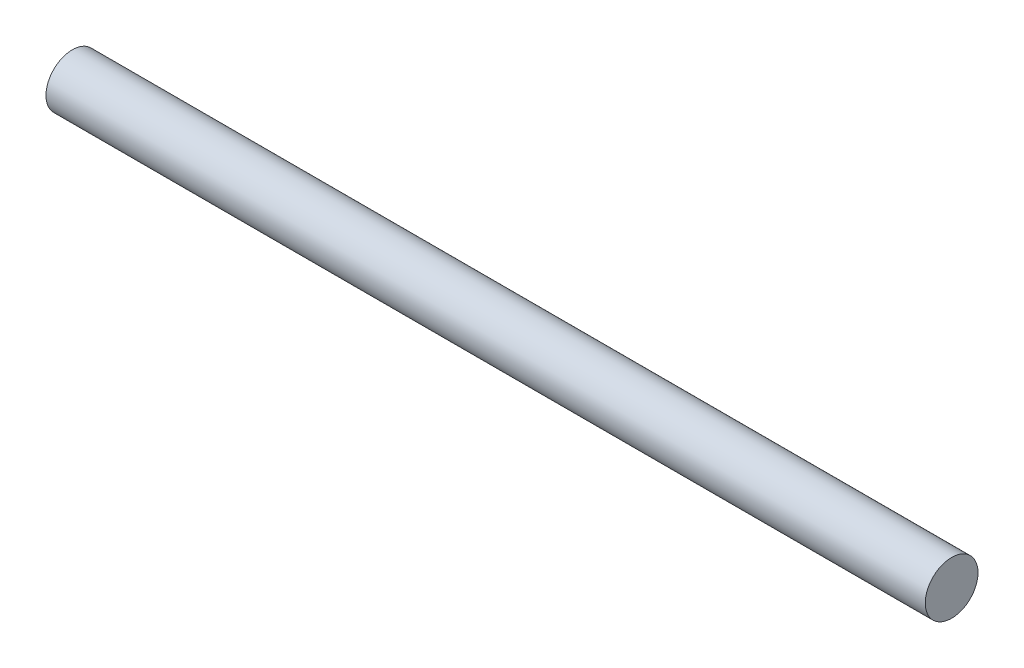
SolidWorks part; units mm, degrees
ref_plane "Front Plane" through (0, 0, 0) normal (0, 0, 1) x (1, 0, 0)
ref_plane "Top Plane" through (0, 0, 0) normal (0, 1, 0) x (1, 0, 0)
ref_plane "Right Plane" through (0, 0, 0) normal (1, 0, 0) x (0, 0, -1)
sketch "Sketch1" plane through (0, 0, 0) normal (1, 0, 0) x (0, 0, -1)
  circle A0 centre (0, 0) radius 6
  dimension "D1" = 12
extrude "Boss-Extrude1" add sketch "Sketch1" along normal blind 200 contours A0
equation "\"WheelDiameter\" = 150mm"
equation "\"WheelRadius\" = \"WheelDiameter\" / 2"
equation "\"DT_WheelWidth\" = 45mm"
equation "\"DT_Wheelbase\" = 300mm"
equation "\"DT_ShaftDiameter\" = 12mm"
equation "\"DT_FrontShaftLength\" = 180mm"
equation "\"DT_RearShaftLength\" = 200mm"
equation "\"DT_BearingWidth\" = 20mm"
equation "\"DT_BearingHousingWidth\" = 60mm"
equation "\"DT_BearingHousingHeight\" = 35mm"
equation "\"DT_ChainPitch\" = 9.525mm"
equation "\"DT_SprocketTeeth\" = 18"
equation "\"DT_SprocketPitchDiameter\" = 54.851mm"
equation "\"DT_SprocketOuterDiameter\" = 60mm"
equation "\"DT_SprocketThickness\" = 6mm"
equation "\"DT_SprocketHubDiameter\" = 25mm"
equation "\"DT_SprocketHubLength\" = 20mm"
equation "\"DT_CouplingDiameter\" = 30mm"
equation "\"DT_CouplingLength\" = 35mm"
equation "\"DT_MotorDiameter\" = 60mm"
equation "\"DT_MotorLength\" = 120mm"
equation "\"DT_MotorShaftDiameter\" = 8mm"
equation "\"DT_MotorShaftLength\" = 20mm"
